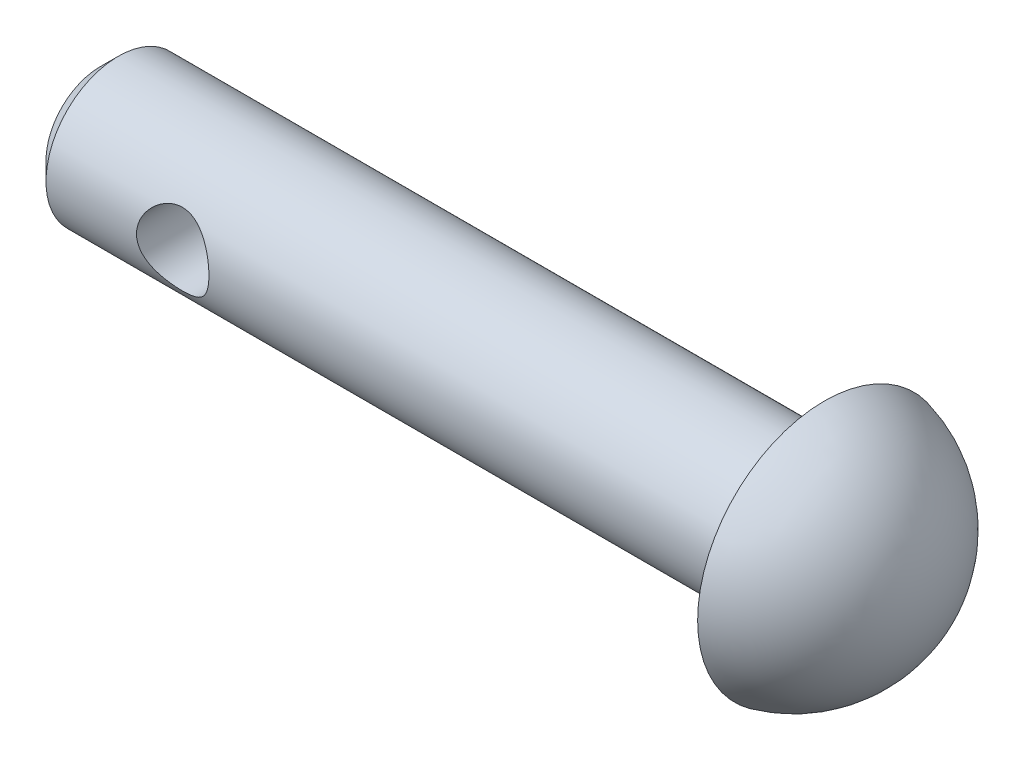
SolidWorks part; units mm, degrees
material "AISI 4340 Steel, annealed"
ref_plane "Front Plane" through (0, 0, 0) normal (0, 0, 1) x (1, 0, 0)
ref_plane "Top Plane" through (0, 0, 0) normal (0, 1, 0) x (1, 0, 0)
ref_plane "Right Plane" through (0, 0, 0) normal (1, 0, 0) x (0, 0, -1)
sketch "Sketch1" plane through (0, 0, 0) normal (1, 0, 0) x (0, 0, -1)
  circle A0 centre (0, 0) radius 2
  dimension "D1" = 4
extrude "Boss-Extrude1" add sketch "Sketch1" along normal mid plane 20
chamfer "Chamfer1" distance 0.5 angle 45 1 edges at (-10, 0, -2)
sketch "Sketch2" plane through (0, 0, 0) normal (0, 0, 1) x (1, 0, 0)
  line L0 (9.1574, 0) -> (12.7574, 0) construction
  line L1 (10, 0) -> (10, 3.5)
  line L2 (10, -2) -> (10, 2) construction
  line L3 (12.7574, 0) -> (10, 0)
  arc A0 (10, 3.5) -> (12.7574, 0) centre (9.1574, 0) cw
  dimension "D1" = 3.6
  dimension "D2" = 3.5
revolve "Revolve1" add sketch "Sketch2" angle 360 about L0
sketch "Sketch3" plane through (0, 0, 0) normal (0, 0, 1) x (1, 0, 0)
  line L0 (10, 2) -> (10, -2) construction
  circle A0 centre (-6, 0) radius 1
  dimension "D1" = 2
  dimension "D2" = 16
extrude "Cut-Extrude1" cut sketch "Sketch3" against normal through all both and the other way through all
